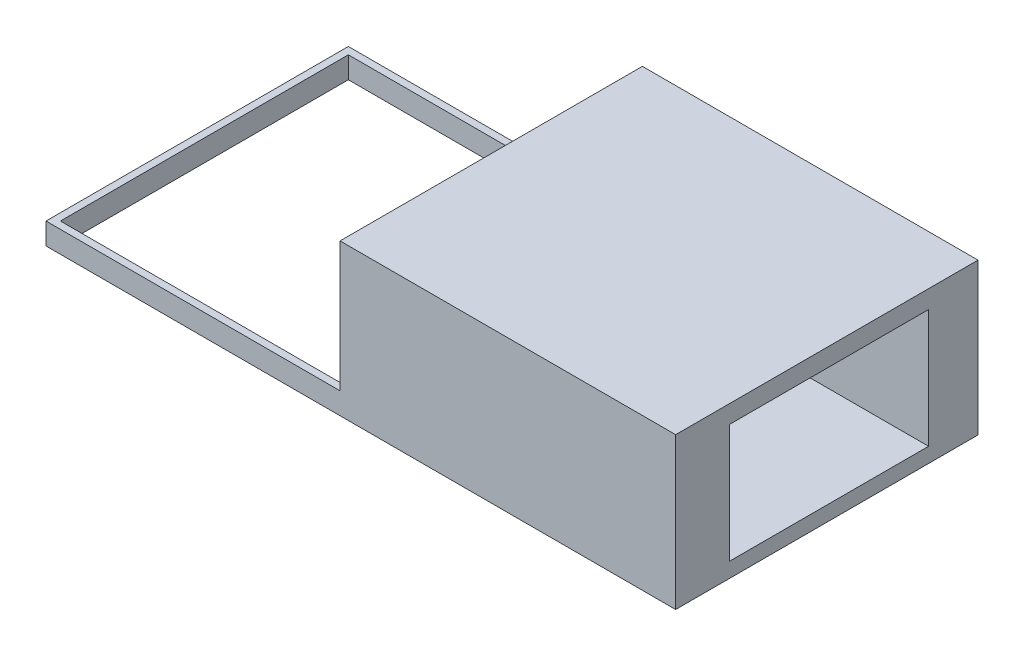
SolidWorks part; units mm, degrees
ref_plane "Alzado" through (0, 0, 0) normal (0, 0, 1) x (1, 0, 0)
ref_plane "Planta" through (0, 0, 0) normal (0, 1, 0) x (1, 0, 0)
ref_plane "Vista lateral" through (0, 0, 0) normal (1, 0, 0) x (0, 0, -1)
sketch "Croquis1" plane through (0, 0, 0) normal (0, 1, 0) x (1, 0, 0)
  line L1 (0, -4.2126) -> (62.3134, -4.2126)
  line L2 (0, -4.2126) -> (0, 37.7122)
  line L3 (0, 37.7122) -> (62.3134, 37.7122)
  line L4 (62.3134, -4.2126) -> (62.3134, 37.7122)
  line L5 (1, -3.2126) -> (61.3134, -3.2126)
  line L6 (1, -3.2126) -> (1, 36.7122)
  line L7 (1, 36.7122) -> (61.3134, 36.7122)
  line L8 (61.3134, -3.2126) -> (61.3134, 36.7122)
  dimension "D1" = 1
  dimension "D2" = 1
  dimension "D3" = 1
  dimension "D4" = 1
extrude "Saliente-Extruir1" add sketch "Croquis1" along normal blind 3
sketch "Croquis3" plane through (0, 3, 0) normal (0, 1, 0) x (1, 0, 0)
  line L0 (40.7751, -4.2126) -> (40.7751, 37.7122)
  line L3 (40.7751, 37.7122) -> (42.1328, 37.7122)
  line L4 (42.1328, 37.7122) -> (42.1328, -4.2126)
  line L5 (42.1328, -4.2126) -> (40.7751, -4.2126)
  line L6 (0, -4.2126) -> (62.3134, -4.2126) construction
  line L8 (62.3134, 37.7122) -> (0, 37.7122) construction
  line L9 (42.1328, -4.2126) -> (62.3134, -4.2126)
  line L10 (62.3134, -4.2126) -> (62.3134, 37.7122)
  line L11 (62.3134, -4.2126) -> (62.3134, 37.7122) construction
  line L12 (62.3134, 37.7122) -> (42.1328, 37.7122)
  line L13 (42.1328, 36.7122) -> (61.3134, 36.7122)
  line L14 (61.3134, 36.7122) -> (1, 36.7122) construction
  line L15 (61.3134, 36.7122) -> (61.3134, -3.2126)
  line L16 (61.3134, -3.2126) -> (42.1328, -3.2126)
  line L17 (1, -3.2126) -> (61.3134, -3.2126) construction
  line M6 (0, -4.2126) -> (62.3134, -4.2126)
  line M7 (62.3134, -4.2126) -> (62.3134, 37.7122)
  line M8 (62.3134, 37.7122) -> (0, 37.7122)
  line M10 (1, 36.7122) -> (61.3134, 36.7122)
  line M11 (61.3134, 36.7122) -> (61.3134, -3.2126)
  line M12 (61.3134, -3.2126) -> (1, -3.2126)
extrude "Saliente-Extruir2" add sketch "Croquis3" along normal blind 18 contours L4 L0 M10 M12 | L4 M8 M10 M11 M12 M6 M7 | L4 L0 M12 M6 | L4 L0 M8 M10
sketch "Croquis4" plane through (40.7751, 0, 0) normal (-1, 0, 0) x (0, 0, 1)
  circle A0 centre (-17.2425, 11.5424) radius 2.5
extrude "Cortar-Extruir1" cut sketch "Croquis4" against normal through all
sketch "Croquis5" plane through (0, 0, -36.7122) normal (0, 0, 1) x (1, 0, 0)
  line L0 (61.3134, 21) -> (61.3134, 0) construction
  line L1 (42.1328, 21) -> (61.3134, 21)
  line L2 (42.1328, 21) -> (42.1328, 19.999)
  line L3 (42.1328, 19.999) -> (61.3134, 19.999)
  line L4 (61.3134, 21) -> (61.3134, 19.999)
extrude "Saliente-Extruir3" add sketch "Croquis5" along normal blind 40
sketch "Croquis6" plane through (62.3134, 0, 0) normal (1, 0, 0) x (0, 0, -1)
  line L1 (3.272, 18.4953) -> (30.8576, 18.4953)
  line L2 (3.272, 18.4953) -> (3.272, 2.0702)
  line L3 (3.272, 2.0702) -> (30.8576, 2.0702)
  line L4 (30.8576, 18.4953) -> (30.8576, 2.0702)
extrude "Cortar-Extruir2" cut sketch "Croquis6" against normal blind 5
sketch "Croquis7" plane through (62.3134, 0, 0) normal (1, 0, 0) x (0, 0, -1)
  line L0 (-4.2126, 21) -> (37.7122, 21)
  line L1 (37.7122, 21) -> (37.7122, 0)
  line L2 (37.7122, 0) -> (-4.2126, 0)
  line L3 (-4.2126, 0) -> (-4.2126, 21)
  line L4 (3.272, 18.4953) -> (3.272, 2.0702)
  line L5 (3.272, 2.0702) -> (30.8576, 2.0702)
  line L6 (30.8576, 2.0702) -> (30.8576, 18.4953)
  line L7 (30.8576, 18.4953) -> (3.272, 18.4953)
extrude "Saliente-Extruir4" add sketch "Croquis7" along normal blind 25
